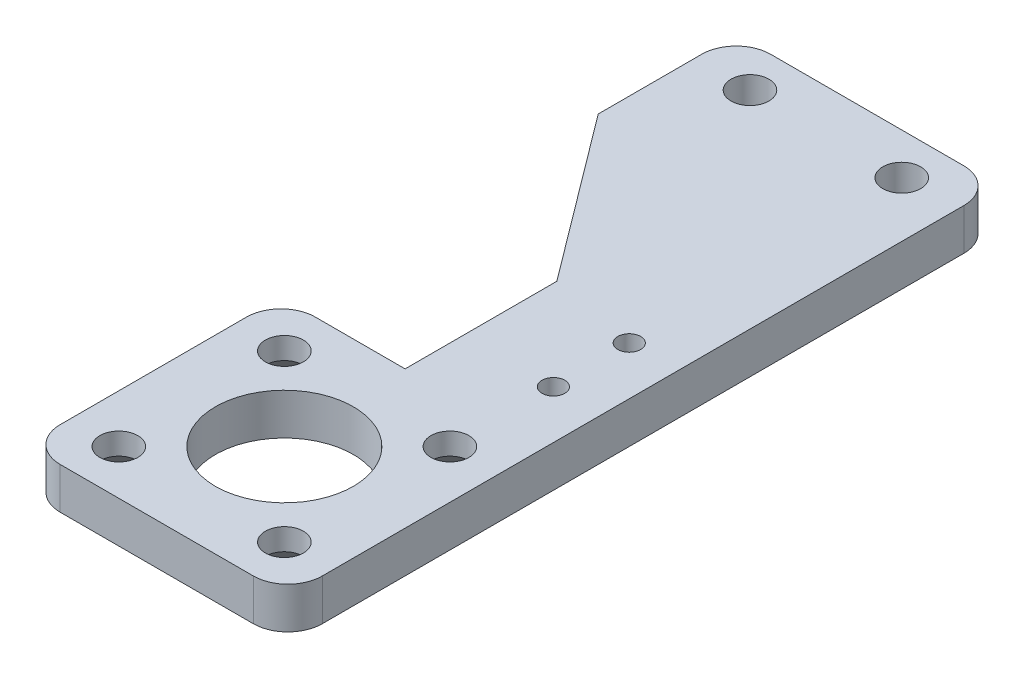
SolidWorks part; units mm, degrees
ref_plane "前视基准面" through (0, 0, 0) normal (0, 0, 1) x (1, 0, 0)
ref_plane "上视基准面" through (0, 0, 0) normal (0, 1, 0) x (1, 0, 0)
ref_plane "右视基准面" through (0, 0, 0) normal (1, 0, 0) x (0, 0, -1)
sketch "草图1" plane through (0, 0, 0) normal (0, 1, 0) x (1, 0, 0)
  line L0 (0, 0) -> (0, 62.9115) construction
  line L1 (-19, 51.5) -> (19, 51.5)
  line L2 (-19, 51.5) -> (-19, -51.5)
  line L3 (-19, -51.5) -> (19, -51.5)
  line L4 (19, 51.5) -> (19, -51.5)
  line L5 (0, 0) -> (103.1394, 0) construction
  dimension "D1" = 38
  dimension "D2" = 103
extrude "凸台-拉伸1" add sketch "草图1" along normal mid plane 6
sketch "草图2" plane through (0, 3, 0) normal (0, 1, 0) x (1, 0, 0)
  line L0 (-19, -14.5) -> (-1, -14.5)
  line L1 (-19, 51.5) -> (-19, -51.5) construction
  line L2 (-1, -14.5) -> (-1, 7.5)
  line L3 (-1, 7.5) -> (-19, 31.5)
  line L4 (-19, 31.5) -> (-19, -14.5)
  line L5 (-19, -51.5) -> (19, -51.5) construction
  line L6 (19, -51.5) -> (19, 51.5) construction
  dimension "D1" = 37
  dimension "D2" = 20
  dimension "D3" = 24
  dimension "D4" = 20
extrude "切除-拉伸1" cut sketch "草图2" against normal through all
sketch "草图3" plane through (0, 3, 0) normal (0, 1, 0) x (1, 0, 0)
  line L0 (-19, -51.5) -> (19, -51.5) construction
  circle A0 centre (0, -33) radius 10
  dimension "D2" = 20
  dimension "D1" = 18.5
extrude "切除-拉伸2" cut sketch "草图3" against normal through all
hole_wizard "M5 六角凹锥坑螺钉的锥形沉头孔1" positions "草图5" profile "草图4" countersink size "M5" standard "ISO" end condition through all
sketch "草图5" plane through (0, -3, 0) normal (0, -1, 0) x (1, 0, 0)
  line L0 (0, 33) -> (0, 56.3131) construction
  line L2 (0, 33) -> (-32.861, 33) construction
  point P0 (12, 45)
  point P1 (-12, 45)
  point P3 (-12, 21)
  point P5 (12, 21)
  dimension "D1" = 24
  dimension "D2" = 24
sketch "草图4" plane through (12, -3, 45) normal (1, 0, 0) x (0, 0, -1)
  line L0 (0, 0) -> (0, 6)
  line L1 (0, 6) -> (2.75, 6)
  line L2 (2.75, 6) -> (2.75, 2.85)
  line L3 (2.75, 2.85) -> (5.6, 0)
  line L5 (5.6, 0) -> (0, 0)
  line L6 (-2.75, 2.85) -> (-5.6, 0) construction
  line L11 (0, -6.35) -> (0, 107.95) construction
  dimension "通孔孔直径" = 5.5
  dimension "通孔孔深度" = 6
  dimension "近端锥形沉头孔直径" = 11.2
  dimension "近端锥形沉头孔角度" = 90
hole_wizard "M4x0.7 螺纹孔1" positions "草图7" profile "草图6" tap size "M4x0.7" standard "JIS"
sketch "草图7" plane through (0, 3, 0) normal (0, 1, 0) x (-1, 0, 0)
  line L0 (-19, -51.5) -> (19, -51.5) construction
  line L1 (-19, 51.5) -> (-19, -51.5) construction
  point P0 (-12, -5)
  point P1 (-12, 6)
  dimension "D1" = 11
  dimension "D2" = 46.5
  dimension "D3" = 7
sketch "草图6" plane through (12, 3, -5) normal (1, 0, 0) x (0, 0, 1)
  line L0 (0, 0) -> (0, 11.0914)
  line L1 (0, 11.0914) -> (1.65, 10.1)
  line L2 (1.65, 10.1) -> (1.65, 0)
  line L5 (1.65, 0) -> (0, 0)
  line L10 (0, 11.0914) -> (-1.65, 10.1) construction
  line L11 (0, -6.35) -> (0, 107.95) construction
  dimension "螺纹孔钻头直径" = 3.3
  dimension "螺纹孔钻头深度" = 10.1
  dimension "导头角度" = 118
cosmetic thread "孔螺蚊线1" parameters "D1"=6, "D2"=4
cosmetic thread "孔螺蚊线2" parameters "D1"=6, "D2"=4
sketch "草图8" plane through (0, 3, 0) normal (0, 1, 0) x (1, 0, 0)
  line L1 (19, 51.5) -> (-19, 51.5) construction
  line L2 (0, 0) -> (0, 48.5992) construction
  circle A0 centre (-11, 45.5) radius 2.75
  circle A1 centre (11, 45.5) radius 2.75
  dimension "D4" = 5.5
  dimension "D2" = 22
  dimension "D3" = 6
extrude "切除-拉伸3" cut sketch "草图8" against normal through all
fillet "圆角1" radius 5 5 edges at (-19, 0, 14.5) (-19, 0, -51.5) (19, 0, -51.5) (-19, 0, 51.5) (19, 0, 51.5)
